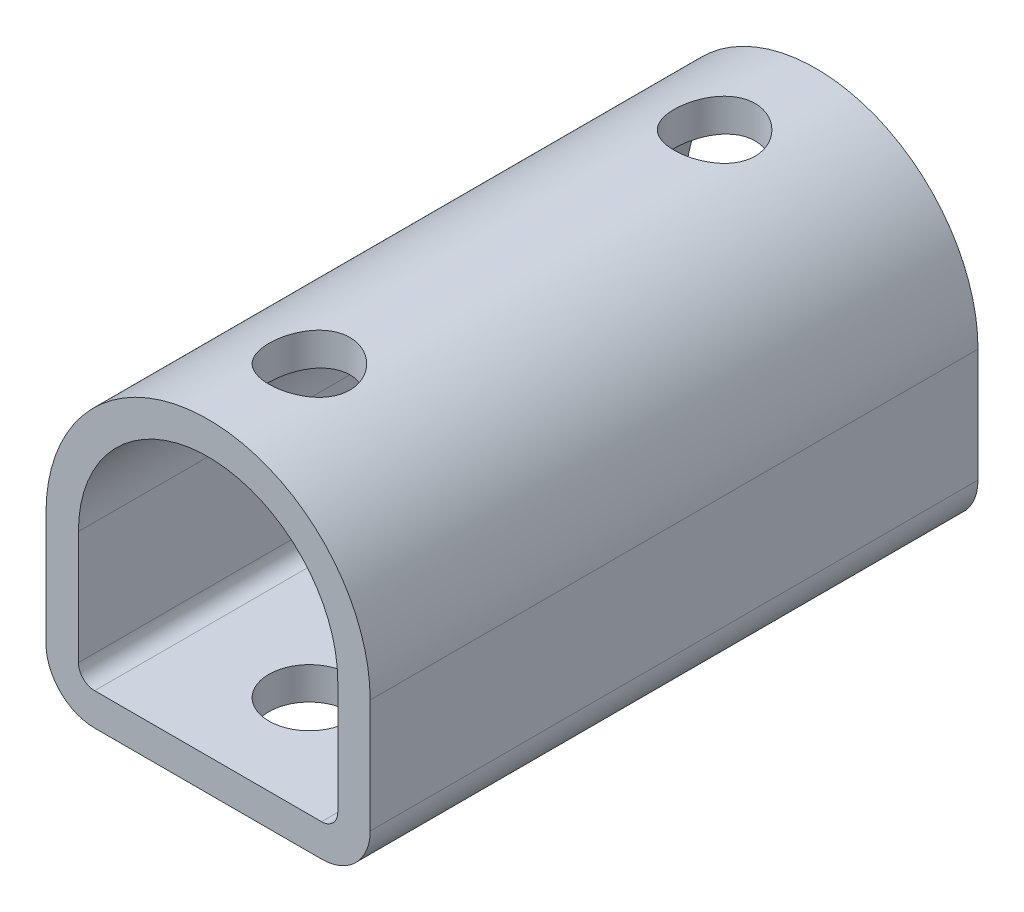
SolidWorks part; units mm, degrees
ref_plane "Front Plane" through (0, 0, 0) normal (0, 0, 1) x (1, 0, 0)
ref_plane "Top Plane" through (0, 0, 0) normal (0, 1, 0) x (1, 0, 0)
ref_plane "Right Plane" through (0, 0, 0) normal (1, 0, 0) x (0, 0, -1)
sketch "Sketch1" plane through (0, 0, 0) normal (0, 0, 1) x (1, 0, 0)
  line L0 (-20, 0) -> (-20, -14)
  line L1 (-14, -20) -> (14, -20)
  line L2 (20, -14) -> (20, 0)
  line L3 (-16, 0) -> (-16, -14)
  line L4 (-14, -16) -> (14, -16)
  line L5 (16, -14) -> (16, 0)
  arc A0 (20, 0) -> (-20, 0) centre (0, 0) ccw
  arc A1 (14, -20) -> (20, -14) centre (14, -14) ccw
  arc A2 (-20, -14) -> (-14, -20) centre (-14, -14) ccw
  arc A3 (16, 0) -> (-16, 0) centre (0, 0) ccw
  arc A4 (-16, -14) -> (-14, -16) centre (-14, -14) ccw
  arc A5 (14, -16) -> (16, -14) centre (14, -14) ccw
  dimension "D1" = 40
  dimension "D3" = 6
  dimension "D2" = 20
  dimension "D4" = 4
extrude "Boss-Extrude2" add sketch "Sketch1" along normal mid plane 75
hole_wizard "Ø10.0 (10) Diameter Hole1" positions "Sketch3" profile "Sketch2" hole size "Ø10.0" standard "ANSI Metric" end condition through all
sketch "Sketch3" plane through (0, -20, 0) normal (0, -1, 0) x (-1, 0, 0)
  line L0 (0, 0) -> (31.8685, 0) construction
  point P0 (0, 25)
  point P2 (0, -25)
  dimension "D1" = 50
sketch "Sketch2" plane through (0, -20, -25) normal (1, 0, 0) x (0, 0, -1)
  line L0 (0, 0) -> (0, 40)
  line L1 (0, 40) -> (5, 40)
  line L2 (5, 40) -> (5, 0)
  line L5 (5, 0) -> (0, 0)
  line L11 (0, -6.35) -> (0, 107.95) construction
  dimension "Thru Hole Dia." = 10
  dimension "Thru Hole Depth" = 40
